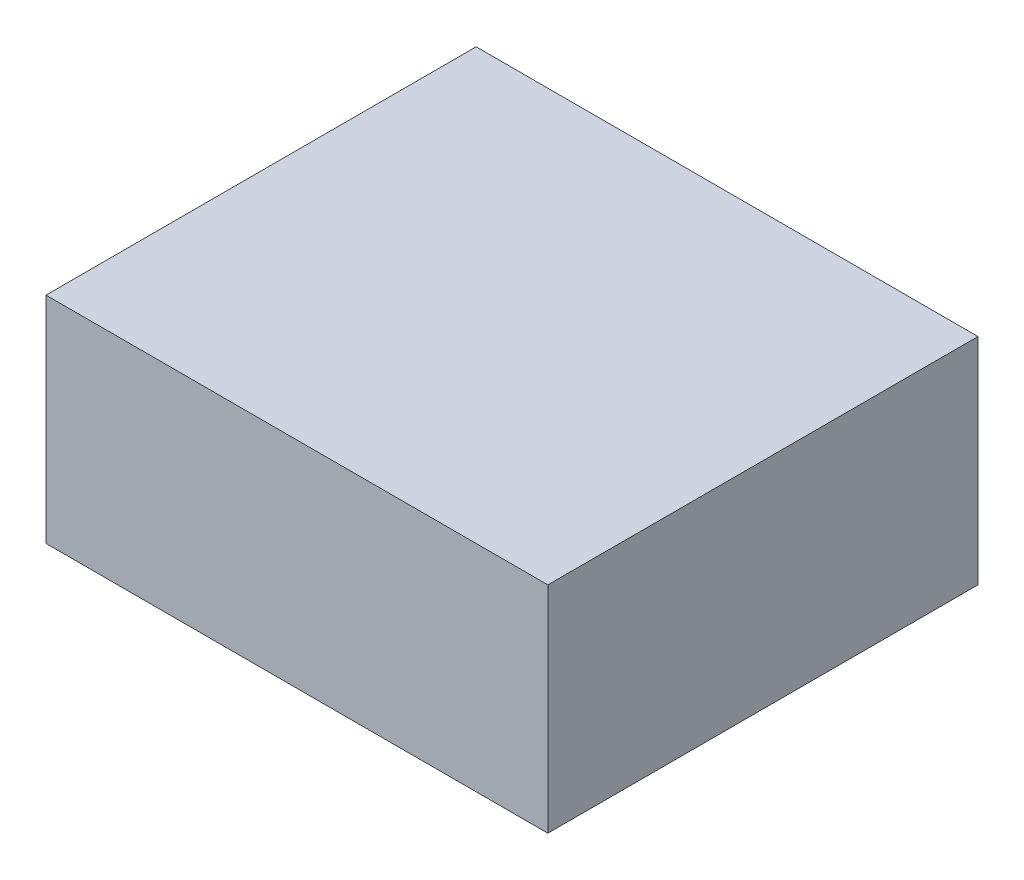
SolidWorks part; units mm, degrees
ref_plane "前视基准面" through (0, 0, 0) normal (0, 0, 1) x (1, 0, 0)
ref_plane "上视基准面" through (0, 0, 0) normal (0, 1, 0) x (1, 0, 0)
ref_plane "右视基准面" through (0, 0, 0) normal (1, 0, 0) x (0, 0, -1)
sketch "草图1" plane through (0, 0, 0) normal (0, 1, 0) x (1, 0, 0)
  line L1 (-35, 30) -> (35, 30)
  line L2 (-35, 30) -> (-35, -30)
  line L3 (-35, -30) -> (35, -30)
  line L4 (35, 30) -> (35, -30)
  dimension "D1" = 70
  dimension "D2" = 60
  dimension "D3" = 35
  dimension "D4" = 30
extrude "凸台-拉伸1" add sketch "草图1" along normal blind 30
